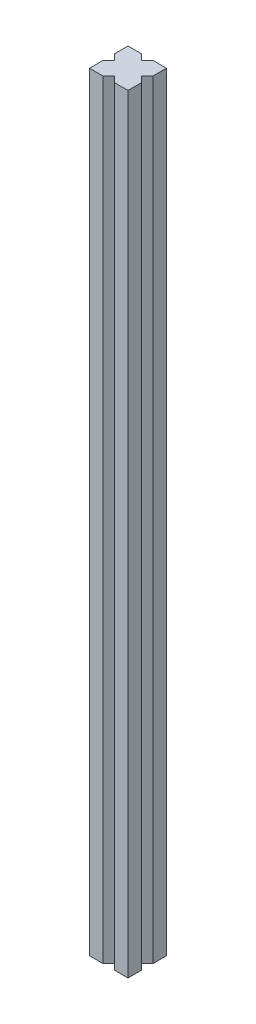
SolidWorks part; units mm, degrees
ref_plane "Front" through (0, 0, 0) normal (0, 0, 1) x (1, 0, 0)
ref_plane "Top" through (0, 0, 0) normal (0, 1, 0) x (1, 0, 0)
ref_plane "Right" through (0, 0, 0) normal (1, 0, 0) x (0, 0, -1)
sketch "Skizze1" plane through (0, 0, 0) normal (0, 1, 0) x (1, 0, 0)
  line L0 (0, 0) -> (0, 20)
  line L1 (0, 20) -> (20, 20)
  line L2 (20, 20) -> (20, 0)
  line L3 (20, 0) -> (0, 0)
  dimension "D1" = 20
extrude "Aufsatz-Linear austragen1" add sketch "Skizze1" along normal blind 400
sketch "Skizze2" plane through (0, 400, 0) normal (0, 1, 0) x (1, 0, 0)
  line L0 (20, 20) -> (0, 20) construction
  line L1 (20, 0) -> (20, 20) construction
  line L4 (0, 20) -> (0, 0) construction
  line L15 (10, 20) -> (10, 0) construction
  line L16 (0, 10) -> (20, 10) construction
  line L17 (7, 20) -> (10, 17)
  line L18 (13, 20) -> (10, 17)
  line L19 (10, 10) -> (20, 20) construction
  line L20 (7, 20) -> (13, 20)
  line L21 (20, 13) -> (17, 10)
  line L22 (20, 7) -> (17, 10)
  line L23 (20, 7) -> (20, 13)
  line L24 (0, 7) -> (0, 13)
  line L25 (0, 7) -> (3, 10)
  line L26 (0, 13) -> (3, 10)
  line L27 (7, 0) -> (13, 0)
  line L28 (13, 0) -> (10, 3)
  line L29 (7, 0) -> (10, 3)
  line L30 (0, 0) -> (20, 0) construction
  dimension "D1" = 3
  dimension "D2" = 3
extrude "Schnitt-Linear austragen1" cut sketch "Skizze2" against normal through all
